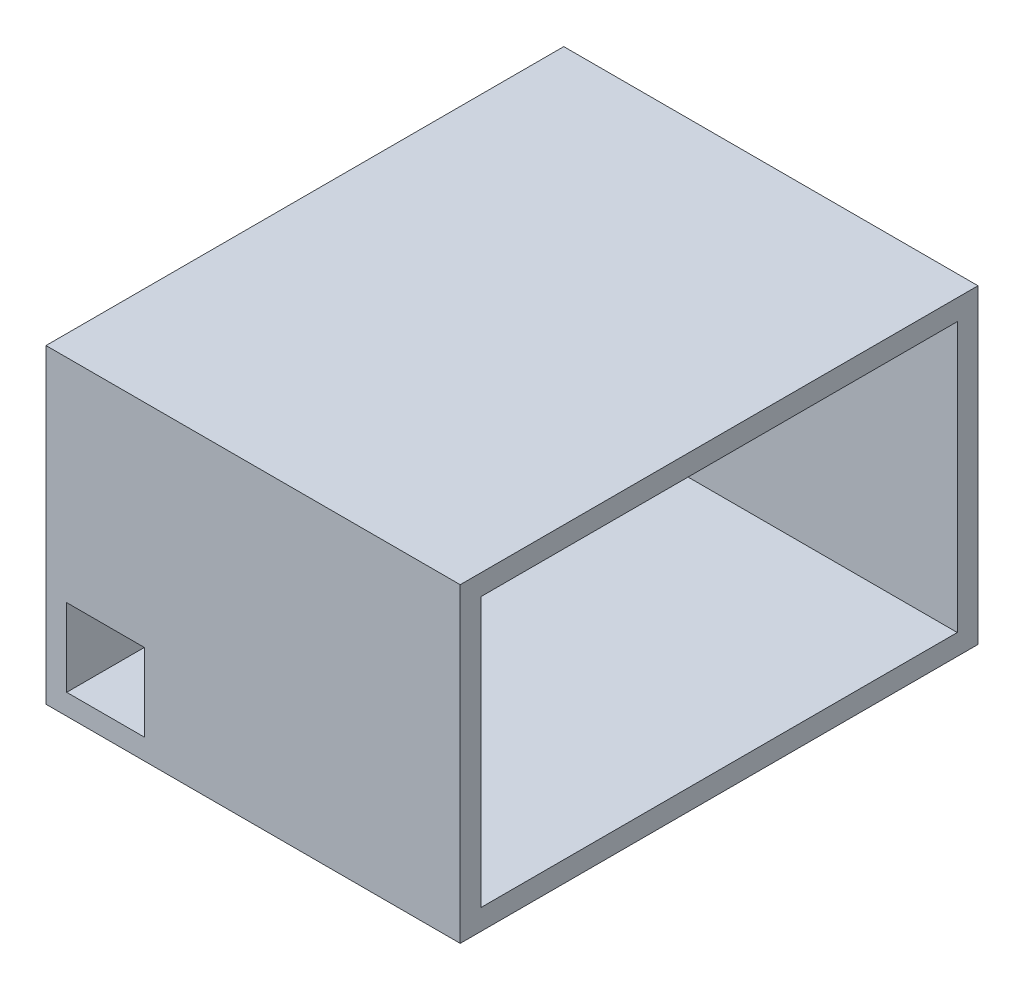
SolidWorks part; units mm, degrees
material "Oak"
ref_plane "Front Plane" through (0, 0, 0) normal (0, 0, 1) x (1, 0, 0)
ref_plane "Top Plane" through (0, 0, 0) normal (0, 1, 0) x (1, 0, 0)
ref_plane "Right Plane" through (0, 0, 0) normal (1, 0, 0) x (0, 0, -1)
sketch "Sketch1" plane through (0, 0, 0) normal (0, 1, 0) x (1, 0, 0)
  line L1 (-40, -50) -> (40, -50)
  line L2 (-40, -50) -> (-40, 50)
  line L3 (-40, 50) -> (40, 50)
  line L4 (40, -50) -> (40, 50)
  line L5 (-40, -50) -> (40, 50) construction
  line L6 (-40, 50) -> (40, -50) construction
  point P0 (0, 0)
  dimension "D1" = 100
  dimension "D2" = 80
extrude "Boss-Extrude1" add sketch "Sketch1" along normal blind 60
sketch "Sketch4" plane through (40, 0, 0) normal (1, 0, 0) x (0, 0, -1)
  line L0 (0, 0) -> (0, 30)
  line L1 (50, 60) -> (50, 0) construction
  line L2 (-46, 56) -> (46, 56)
  line L3 (-46, 56) -> (-46, 4)
  line L4 (-46, 4) -> (46, 4)
  line L5 (46, 56) -> (46, 4)
  line L6 (-46, 56) -> (46, 4) construction
  line L7 (-46, 4) -> (46, 56) construction
  line L8 (-50, 60) -> (50, 60) construction
  dimension "D1" = 30
  dimension "D2" = 4
  dimension "D3" = 4
extrude "Cut-Extrude1" cut sketch "Sketch4" against normal blind 76
sketch "Sketch5" plane through (0, 0, 50) normal (0, 0, 1) x (1, 0, 0)
  line L0 (-36, 0) -> (-36, 4)
  line L1 (-40, 0) -> (40, 0) construction
  line L2 (-40, 60) -> (-40, 0) construction
  line L4 (-36, 4) -> (-21, 4)
  line L5 (-36, 4) -> (-36, 19)
  line L6 (-36, 19) -> (-21, 19)
  line L7 (-21, 4) -> (-21, 19)
  dimension "D1" = 4
  dimension "D2" = 4
  dimension "D3" = 15
  dimension "D4" = 15
extrude "Cut-Extrude2" cut sketch "Sketch5" against normal blind 4 contours L4 L7 L6 L5
